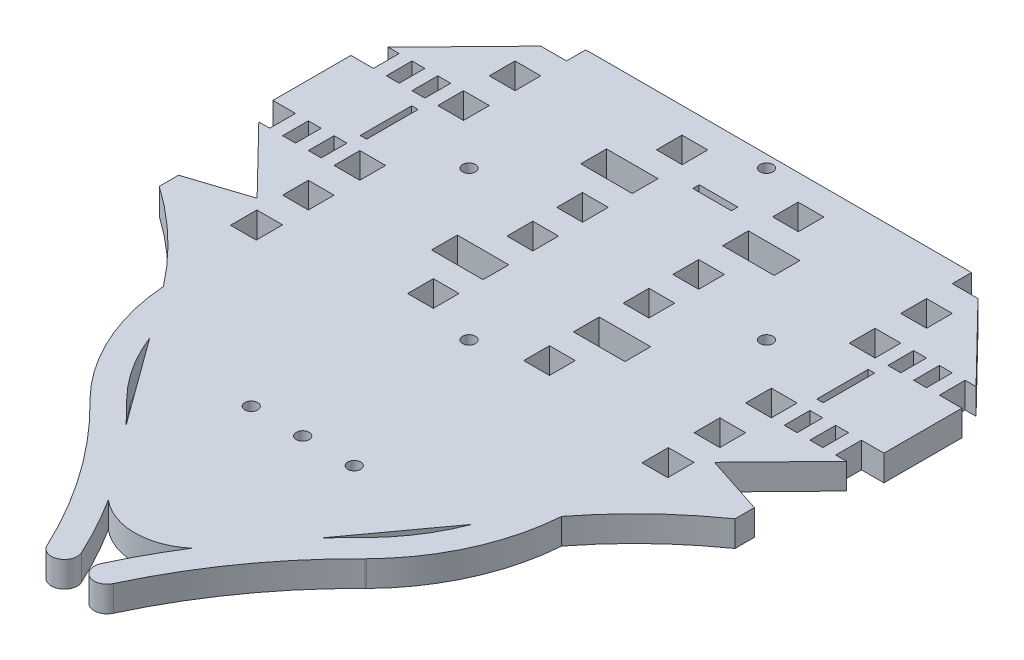
SolidWorks part; units mm, degrees
ref_plane "Front Plane" through (0, 0, 0) normal (0, 0, 1) x (1, 0, 0)
ref_plane "Top Plane" through (0, 0, 0) normal (0, 1, 0) x (1, 0, 0)
ref_plane "Right Plane" through (0, 0, 0) normal (1, 0, 0) x (0, 0, -1)
sketch "Sketch1" plane through (0, 0, 0) normal (0, 1, 0) x (1, 0, 0)
  line L0 (0, 0) -> (0, 190.5) construction
  line L1 (-75.3541, 160.3375) -> (-75.3541, 141.1116)
  line L2 (-11.1506, 184.15) -> (-11.1506, 177.85)
  line L3 (-17.5006, 184.15) -> (-11.1506, 184.15)
  line L4 (47.5742, 185.7375) -> (47.5742, 190.4453)
  line L5 (-53.9242, 160.3375) -> (-53.9242, 166.6875) construction
  line L6 (-31.7501, 150.7245) -> (31.7501, 150.7245) construction
  line L7 (47.5742, 173.0375) -> (47.5742, 179.3875)
  line L8 (-45.218, 190.5) -> (45.218, 190.5)
  line L9 (47.5742, 160.3375) -> (47.5742, 166.6875)
  line L10 (47.5742, 160.3375) -> (47.5742, 141.1116) construction
  line L11 (-39.7923, 75.1534) -> (-23.9247, 53.3989)
  line L12 (47.5742, 141.1116) -> (47.5742, 134.7616)
  line L13 (0, 92.6888) -> (-28.0924, 92.6888) construction
  line L14 (47.5742, 128.4116) -> (47.5742, 122.0616)
  line L15 (-28.0924, 105.9095) -> (-21.7424, 105.9095)
  line L16 (-21.7424, 105.9095) -> (-21.7424, 118.6095)
  line L17 (21.7424, 105.9095) -> (21.7424, 118.6095)
  line L18 (28.0924, 105.9095) -> (21.7424, 105.9095)
  line L19 (11.1506, 184.15) -> (11.1506, 177.85) construction
  line L20 (11.1506, 122.809) -> (11.1506, 116.459)
  line L21 (-17.5006, 184.15) -> (-17.5006, 177.85) construction
  line L22 (-17.5006, 177.85) -> (-11.1506, 177.85)
  line L23 (11.1506, 147.3454) -> (11.1506, 140.9954)
  line L24 (21.7424, 79.4681) -> (21.7424, 66.7681)
  line L25 (28.0924, 79.4681) -> (21.7424, 79.4681)
  line L26 (-21.7424, 79.4681) -> (-21.7424, 66.7681)
  line L27 (-28.0924, 79.4681) -> (-21.7424, 79.4681)
  line L28 (17.5006, 116.459) -> (11.1506, 116.459)
  line L29 (17.5006, 122.809) -> (17.5006, 116.459) construction
  line L30 (17.5006, 122.809) -> (11.1506, 122.809)
  line L31 (11.1506, 159.6136) -> (11.1506, 153.2636)
  line L32 (-17.5006, 159.6136) -> (-11.1506, 159.6136)
  line L33 (-17.5006, 159.6136) -> (-17.5006, 153.2636) construction
  line L34 (-28.0924, 105.9095) -> (-28.0924, 118.6095)
  line L35 (21.7424, 118.6095) -> (28.0924, 118.6095)
  line L36 (28.0924, 105.9095) -> (28.0924, 118.6095)
  line L37 (21.7424, 66.7681) -> (28.0924, 66.7681)
  line L38 (-103.4465, 150.7245) -> (-84.8791, 150.7245) construction
  line L39 (-103.3706, 147.4616) -> (-84.8791, 147.4616) construction
  line L40 (-103.3546, 153.9875) -> (-84.8791, 153.9875) construction
  line L41 (-103.4465, 153.9875) -> (-84.8791, 153.9875) construction
  line L42 (-103.4465, 147.4616) -> (-84.8791, 147.4616) construction
  line L43 (-71.0143, 118.2516) -> (-71.0143, 108.732)
  line L44 (-53.9242, 173.0375) -> (-53.9242, 179.3875)
  line L45 (-53.9242, 160.3375) -> (-53.9242, 166.6875)
  line L46 (-53.9242, 109.2092) -> (-53.9242, 115.7116)
  line L47 (-84.8791, 150.7245) -> (-31.7501, 150.7245) construction
  line L48 (-47.5742, 160.3375) -> (-47.5742, 141.1116) construction
  line L49 (-53.9242, 115.7116) -> (-47.5742, 115.7116)
  line L50 (-72.4971, 166.6875) -> (-53.9242, 185.7375)
  line L51 (-53.9242, 134.7616) -> (-53.9242, 141.1116)
  line L52 (-53.9242, 118.2516) -> (-47.5742, 118.2516) construction
  line L53 (-53.9242, 122.0616) -> (-53.9242, 128.4116)
  line L54 (-57.0992, 134.7616) -> (-57.0992, 141.1116)
  line L55 (47.5742, 115.7116) -> (47.5742, 109.2092)
  line L56 (-71.0143, 118.2516) -> (-56.4006, 118.2516)
  line L57 (-60.2742, 134.7616) -> (-60.2742, 141.1116)
  line L58 (-63.4492, 134.7616) -> (-63.4492, 141.1116)
  line L59 (84.8791, 150.7245) -> (31.7501, 150.7245) construction
  line L60 (-47.5742, 166.6875) -> (-53.9242, 166.6875)
  line L61 (-47.5742, 160.3375) -> (-47.5742, 166.6875)
  line L62 (-47.5742, 160.3375) -> (-53.9242, 160.3375)
  line L63 (-47.5742, 173.0375) -> (-53.9242, 173.0375)
  line L64 (-47.5742, 179.3875) -> (-53.9242, 179.3875)
  line L65 (-47.5742, 185.7375) -> (-53.9242, 185.7375)
  line L66 (-47.5742, 173.0375) -> (-47.5742, 179.3875)
  line L67 (103.3546, 153.9875) -> (84.8791, 153.9875) construction
  line L68 (-47.5742, 185.7375) -> (-47.5742, 190.4453)
  line L69 (-66.6242, 134.7616) -> (-66.6242, 141.1116)
  line L70 (-47.5742, 115.7116) -> (-47.5742, 109.2092)
  line L71 (-69.7992, 134.7616) -> (-69.7992, 141.1116)
  line L72 (-47.5742, 128.4116) -> (-47.5742, 122.0616)
  line L73 (-47.5742, 122.0616) -> (-53.9242, 122.0616)
  line L74 (-47.5742, 128.4116) -> (-53.9242, 128.4116)
  line L75 (-47.5742, 141.1116) -> (-53.9242, 141.1116)
  line L76 (-47.5742, 141.1116) -> (-47.5742, 134.7616)
  line L77 (-47.5742, 134.7616) -> (-53.9242, 134.7616)
  line L78 (-69.7992, 160.3375) -> (-75.3541, 160.3375)
  line L79 (-47.5742, 109.2092) -> (-53.9242, 109.2092)
  line L80 (-17.5006, 153.2636) -> (-11.1506, 153.2636)
  line L81 (-17.5006, 147.3454) -> (-11.1506, 147.3454)
  line L82 (-17.5006, 147.3454) -> (-17.5006, 140.9954) construction
  line L83 (-17.5006, 140.9954) -> (-11.1506, 140.9954)
  line L84 (-11.1506, 159.6136) -> (-11.1506, 153.2636)
  line L85 (-17.5006, 122.809) -> (-11.1506, 122.809)
  line L86 (-17.5006, 122.809) -> (-17.5006, 116.459) construction
  line L87 (-17.5006, 116.459) -> (-11.1506, 116.459)
  line L88 (-11.1506, 147.3454) -> (-11.1506, 140.9954)
  line L89 (-11.1506, 122.809) -> (-11.1506, 116.459)
  line L90 (-57.0992, 134.7616) -> (-60.2742, 134.7616)
  line L91 (-57.0992, 141.1116) -> (-60.2742, 141.1116)
  line L92 (-63.4492, 141.1116) -> (-66.6242, 141.1116)
  line L93 (23.8506, 165.5318) -> (11.1506, 165.5318)
  line L94 (-11.1506, 165.5318) -> (-11.1506, 171.8818)
  line L95 (-23.8506, 171.8818) -> (-11.1506, 171.8818) construction
  line L96 (23.8506, 165.5318) -> (23.8506, 171.8818)
  line L97 (23.8506, 171.8818) -> (11.1506, 171.8818) construction
  line L98 (-23.8506, 165.5318) -> (-23.8506, 171.8818)
  line L99 (11.1506, 165.5318) -> (11.1506, 171.8818)
  line L100 (-23.8506, 165.5318) -> (-11.1506, 165.5318)
  line L101 (-63.4492, 134.7616) -> (-66.6242, 134.7616)
  line L102 (-17.5006, 184.15) -> (-17.5006, 177.85)
  line L103 (-69.7992, 134.7616) -> (-72.4971, 134.7616)
  line L104 (-69.7992, 141.1116) -> (-75.3541, 141.1116)
  line L105 (-23.8506, 150.3045) -> (23.8506, 150.3045) construction
  line L106 (-23.8506, 135.0772) -> (-11.1506, 135.0772)
  line L107 (17.5006, 140.9954) -> (11.1506, 140.9954)
  line L108 (17.5006, 147.3454) -> (17.5006, 140.9954) construction
  line L109 (17.5006, 147.3454) -> (11.1506, 147.3454)
  line L110 (11.1506, 135.0772) -> (11.1506, 128.7272)
  line L111 (17.5006, 153.2636) -> (11.1506, 153.2636)
  line L112 (17.5006, 159.6136) -> (17.5006, 153.2636) construction
  line L113 (17.5006, 159.6136) -> (11.1506, 159.6136)
  line L114 (-23.8506, 135.0772) -> (-23.8506, 128.7272)
  line L115 (23.8506, 128.7272) -> (11.1506, 128.7272) construction
  line L116 (23.8506, 135.0772) -> (23.8506, 128.7272)
  line L117 (-23.8506, 128.7272) -> (-11.1506, 128.7272) construction
  line L118 (-11.1506, 135.0772) -> (-11.1506, 128.7272)
  line L119 (23.8506, 135.0772) -> (11.1506, 135.0772)
  line L120 (17.5006, 177.85) -> (11.1506, 177.85)
  line L121 (17.5006, 184.15) -> (17.5006, 177.85) construction
  line L122 (17.5006, 184.15) -> (11.1506, 184.15)
  line L123 (103.3706, 147.4616) -> (84.8791, 147.4616) construction
  line L124 (103.4465, 150.7245) -> (84.8791, 150.7245) construction
  line L125 (57.0992, 166.6875) -> (57.0992, 160.3375)
  line L126 (60.2742, 166.6875) -> (60.2742, 160.3375)
  line L127 (63.4492, 166.6875) -> (63.4492, 160.3375)
  line L128 (66.6242, 166.6875) -> (66.6242, 160.3375)
  line L129 (69.7992, 166.6875) -> (69.7992, 160.3375)
  line L130 (57.0992, 166.6875) -> (60.2742, 166.6875)
  line L131 (57.0992, 160.3375) -> (60.2742, 160.3375)
  line L132 (63.4492, 160.3375) -> (66.6242, 160.3375)
  line L133 (11.1506, 184.15) -> (11.1506, 177.85)
  line L134 (63.4492, 166.6875) -> (66.6242, 166.6875)
  line L135 (-72.4971, 134.7616) -> (-56.4006, 118.2516)
  line L136 (69.7992, 166.6875) -> (72.4971, 166.6875)
  line L137 (72.4971, 134.7616) -> (56.4006, 118.2516)
  line L138 (69.7992, 141.1116) -> (75.3541, 141.1116)
  line L139 (69.7992, 134.7616) -> (72.4971, 134.7616)
  line L140 (63.4492, 134.7616) -> (66.6242, 134.7616)
  line L141 (63.4492, 141.1116) -> (66.6242, 141.1116)
  line L142 (57.0992, 141.1116) -> (60.2742, 141.1116)
  line L143 (57.0992, 134.7616) -> (60.2742, 134.7616)
  line L144 (47.5742, 109.2092) -> (53.9242, 109.2092)
  line L145 (69.7992, 160.3375) -> (75.3541, 160.3375)
  line L146 (47.5742, 134.7616) -> (53.9242, 134.7616)
  line L147 (-69.7992, 166.6875) -> (-72.4971, 166.6875)
  line L148 (47.5742, 141.1116) -> (53.9242, 141.1116)
  line L149 (47.5742, 128.4116) -> (53.9242, 128.4116)
  line L150 (47.5742, 122.0616) -> (53.9242, 122.0616)
  line L151 (-63.4492, 166.6875) -> (-66.6242, 166.6875)
  line L152 (69.7992, 134.7616) -> (69.7992, 141.1116)
  line L153 (66.6242, 134.7616) -> (66.6242, 141.1116)
  line L154 (47.5742, 185.7375) -> (53.9242, 185.7375)
  line L155 (-63.4492, 160.3375) -> (-66.6242, 160.3375)
  line L156 (47.5742, 179.3875) -> (53.9242, 179.3875)
  line L157 (-57.0992, 160.3375) -> (-60.2742, 160.3375)
  line L158 (-57.0992, 166.6875) -> (-60.2742, 166.6875)
  line L159 (47.5742, 173.0375) -> (53.9242, 173.0375)
  line L160 (-23.8506, 171.8818) -> (-11.1506, 171.8818)
  line L161 (-69.7992, 166.6875) -> (-69.7992, 160.3375)
  line L162 (-66.6242, 166.6875) -> (-66.6242, 160.3375)
  line L163 (-63.4492, 166.6875) -> (-63.4492, 160.3375)
  line L164 (-60.2742, 166.6875) -> (-60.2742, 160.3375)
  line L165 (-57.0992, 166.6875) -> (-57.0992, 160.3375)
  line L166 (-17.5006, 159.6136) -> (-17.5006, 153.2636)
  line L167 (39.7923, 75.1534) -> (23.9247, 53.3989)
  line L168 (47.5742, 160.3375) -> (53.9242, 160.3375)
  line L169 (47.5742, 166.6875) -> (53.9242, 166.6875)
  line L170 (-28.0924, 66.7681) -> (-21.7424, 66.7681)
  line L171 (-28.0924, 66.7681) -> (-28.0924, 79.4681)
  line L172 (63.4492, 134.7616) -> (63.4492, 141.1116)
  line L173 (-28.0924, 118.6095) -> (-21.7424, 118.6095)
  line L174 (28.0924, 66.7681) -> (28.0924, 79.4681)
  line L175 (-28.0924, 66.7681) -> (28.0924, 118.6095) construction
  line L176 (-28.0924, 118.6095) -> (28.0924, 66.7681) construction
  line L177 (-17.5006, 147.3454) -> (-17.5006, 140.9954)
  line L178 (60.2742, 134.7616) -> (60.2742, 141.1116)
  line L179 (71.0143, 118.2516) -> (56.4006, 118.2516)
  line L180 (57.0992, 134.7616) -> (57.0992, 141.1116)
  line L181 (53.9242, 122.0616) -> (53.9242, 128.4116)
  line L182 (53.9242, 134.7616) -> (53.9242, 141.1116)
  line L183 (72.4971, 166.6875) -> (53.9242, 185.7375)
  line L184 (-23.8506, 128.7272) -> (-11.1506, 128.7272)
  line L185 (53.9242, 115.7116) -> (47.5742, 115.7116)
  line L186 (53.9242, 109.2092) -> (53.9242, 115.7116)
  line L187 (-17.5006, 122.809) -> (-17.5006, 116.459)
  line L188 (53.9242, 160.3375) -> (53.9242, 166.6875)
  line L189 (53.9242, 173.0375) -> (53.9242, 179.3875)
  line L190 (71.0143, 118.2516) -> (71.0143, 108.732)
  line L191 (17.5006, 116.459) -> (17.5006, 122.809)
  line L192 (75.3541, 160.3375) -> (75.3541, 141.1116)
  line L193 (57.0992, 157.0745) -> (55.5117, 157.0745)
  line L194 (11.1506, 128.7272) -> (23.8506, 128.7272)
  line L195 (-14.3256, 184.15) -> (-14.3256, 190.5) construction
  line L196 (-14.3256, 187.325) -> (14.3256, 187.325) construction
  line L197 (57.0992, 144.3745) -> (57.0992, 157.0745)
  line L198 (55.5117, 144.3745) -> (55.5117, 157.0745)
  line L199 (17.5006, 140.9954) -> (17.5006, 147.3454)
  line L200 (-55.5117, 144.3745) -> (-57.0992, 144.3745)
  line L201 (-55.5117, 144.3745) -> (-55.5117, 157.0745)
  line L202 (-57.0992, 157.0745) -> (-55.5117, 157.0745)
  line L203 (17.5006, 153.2636) -> (17.5006, 159.6136)
  line L204 (55.5117, 144.3745) -> (57.0992, 144.3745)
  line L205 (-11.1506, 177.85) -> (-11.1506, 171.8818) construction
  line L206 (11.1506, 171.8818) -> (23.8506, 171.8818)
  line L207 (-11.1506, 174.8659) -> (0, 174.8659) construction
  line L208 (-57.0992, 144.3745) -> (-57.0992, 157.0745)
  line L210 (-4.7625, 174.0722) -> (4.7625, 174.0722)
  line L211 (17.5006, 177.85) -> (17.5006, 184.15)
  line L212 (-4.7625, 174.0722) -> (-4.7625, 175.6597)
  line L213 (-4.7625, 175.6597) -> (4.7625, 175.6597)
  line L214 (4.7625, 174.0722) -> (4.7625, 175.6597)
  line L215 (-72.9742, 135.2509) -> (-72.9742, 141.1116) [skipped]
  line L216 (-21.7424, 73.1181) -> (21.7424, 73.1181) construction
  line L217 (-4.7625, 174.0722) -> (4.7625, 175.6597) construction
  line L218 (-4.7625, 175.6597) -> (4.7625, 174.0722) construction
  arc A0 (-98.3796, 168.1096) -> (-103.3546, 153.9875) centre (-71.7653, 150.7966) ccw construction
  arc A1 (-10.307, 35.463) -> (10.307, 35.463) centre (0, 47.625) ccw
  arc A2 (-103.3706, 147.4616) -> (-78.8191, 113.9815) centre (-63.8175, 150.7245) ccw construction
  arc A3 (-70.6509, 186.2152) -> (-98.3796, 168.1096) centre (-67.31, 150.8125) ccw construction
  arc A4 (-71.0143, 108.732) -> (-49.1129, 87.8559) centre (-129.382, 25.5708) cw
  arc A5 (47.5742, 190.4453) -> (45.218, 190.5) centre (45.218, 139.7) ccw
  arc A6 (66.2518, 115.2682) -> (31.7501, 150.7245) centre (67.31, 150.8125) cw construction
  arc A7 (-67.31, 186.3725) -> (-31.7501, 150.7245) centre (-67.31, 150.8125) cw construction
  arc A8 (-66.2518, 115.2682) -> (-31.7501, 150.7245) centre (-67.31, 150.8125) ccw construction
  arc A9 (67.31, 186.3725) -> (31.7501, 150.7245) centre (67.31, 150.8125) ccw construction
  arc A10 (70.6509, 186.2152) -> (98.3796, 168.1096) centre (67.31, 150.8125) cw construction
  arc A11 (103.3706, 147.4616) -> (78.8191, 113.9815) centre (63.8175, 150.7245) cw construction
  arc A12 (98.3796, 168.1096) -> (103.3546, 153.9875) centre (71.7653, 150.7966) cw construction
  arc A13 (71.0143, 108.732) -> (49.1129, 87.8559) centre (129.382, 25.5708) ccw
  arc A14 (23.9247, 53.3989) -> (29.4574, 59.1474) centre (120.746, -34.2501) cw
  arc A15 (34.0855, 54.7275) -> (33.9333, 54.5681) centre (31.6954, 56.8578) cw
  arc A16 (39.7923, 75.1534) -> (29.5378, 59.2233) centre (-3.4651, 91.7334) cw
  arc A17 (-47.5742, 190.4453) -> (-45.218, 190.5) centre (-45.218, 139.7) cw
  arc A18 (-2.3792, 20.9404) -> (-10.307, 35.463) centre (-120.746, -34.2501) ccw
  arc A19 (-8.1827, 18.2344) -> (-33.9333, 54.5681) centre (-120.746, -34.2501) ccw
  arc A20 (-8.1827, 18.2344) -> (-2.3792, 20.9404) centre (-5.2809, 19.5874) ccw
  arc A21 (-29.4574, 59.1474) -> (-29.5378, 59.2233) centre (-31.6954, 56.8578) ccw
  circle A22 centre (0, 150.7245) radius 36.6005 construction
  arc A23 (-49.1129, 87.8559) -> (-34.0855, 54.7275) centre (3.4651, 91.7334) ccw
  arc A24 (-39.7923, 75.1534) -> (-29.5378, 59.2233) centre (3.4651, 91.7334) ccw
  arc A25 (-34.0855, 54.7275) -> (-33.9333, 54.5681) centre (-31.6954, 56.8578) ccw
  arc A26 (-23.9247, 53.3989) -> (-29.4574, 59.1474) centre (-120.746, -34.2501) ccw
  arc A27 (49.1129, 87.8559) -> (34.0855, 54.7275) centre (-3.4651, 91.7334) cw
  circle A28 centre (0, 114.1241) radius 1.5875
  arc A29 (29.4574, 59.1474) -> (29.5378, 59.2233) centre (31.6954, 56.8578) cw
  circle A30 centre (-36.6884, 150.8125) radius 1.5875
  arc A31 (8.1827, 18.2344) -> (2.3792, 20.9404) centre (5.2809, 19.5874) cw
  arc A32 (8.1827, 18.2344) -> (33.9333, 54.5681) centre (120.746, -34.2501) cw
  arc A33 (2.3792, 20.9404) -> (10.307, 35.463) centre (120.746, -34.2501) cw
  circle A34 centre (0, 73.1031) radius 1.5875
  circle A35 centre (12.7, 73.1031) radius 1.5875
  circle A36 centre (0, 187.5009) radius 1.5875
  circle A37 centre (36.6884, 150.8125) radius 1.5875
  circle A38 centre (-12.7, 73.1031) radius 1.5875
  point P28 (-51.906, 190.5)
  point P30 (-67.31, 186.3725)
  point P32 (0, 150.8125)
  point P50 (-16.804, 39.5041)
  point P55 (-40.3772, 68.7904)
  point P67 (0, 75.2413)
  point P69 (0, 150.7245)
  point P96 (0, 92.6888)
  point P151 (0, 168.7068)
  point P154 (-14.3256, 168.7068)
  point P156 (-23.8506, 168.7068)
  point P177 (14.3256, 168.7068)
  point P180 (-23.8506, 150.3045)
  point P183 (-14.3256, 131.9022)
  point P211 (-53.9242, 150.7245)
  point P233 (14.3256, 131.9022)
  point P235 (0, 131.9022)
  point P256 (40.3772, 68.7904)
  point P257 (16.804, 39.5041)
  point P258 (53.9242, 150.7245)
  point P269 (-55.5117, 150.7245)
  point P271 (0, 178.6438)
  point P285 (0, 150.8125)
  point P289 (0, 180.975)
  dimension "D4" = 6.35
  dimension "D5" = 51.8414
  dimension "D6" = 56.1848
  dimension "D7" = 79.375
  dimension "D8" = 71.12
  dimension "D9" = 12.7
  dimension "D11" = 2.54
  dimension "D12" = 6
  dimension "D13" = 9.525
  dimension "D14" = 3.175
  dimension "D17" = 1.5875
  dimension "D3" = 4
  dimension "D10" = 3.175
  dimension "D16" = 18.5674
  dimension "D19" = 6.35
  dimension "D23" = 2
  dimension "D18" = 6.35
  dimension "D20" = 6.35
  dimension "D15" = 1.5875
  dimension "D21" = 12.7
  dimension "D22" = 2
  dimension "D24" = 2
extrude "Boss-Extrude1" add sketch "Sketch1" along normal blind 6.35
sketch "Sketch2" plane through (0, 6.35, 0) normal (0, 1, 0) x (1, 0, 0)
  line L0 (-56.4006, 118.2516) -> (-71.0143, 118.2516)
  line L1 (-71.0143, 118.2516) -> (-71.0143, 113.4918)
  line L2 (-71.0143, 118.2516) -> (-71.0143, 108.732) construction
  line L3 (-71.0143, 113.4918) -> (-56.4006, 118.2516)
  line L4 (0, 189.0884) -> (0, 90.2888) construction
  line L5 (71.0143, 113.4918) -> (56.4006, 118.2516)
  line L6 (71.0143, 118.2516) -> (71.0143, 113.4918)
  line L7 (56.4006, 118.2516) -> (71.0143, 118.2516)
  circle A0 centre (0, 187.5009) radius 1.5875 construction
extrude "Cut-Extrude1" cut sketch "Sketch2" against normal through all
sketch "Sketch3" plane through (0, 6.35, 0) normal (0, 1, 0) x (1, 0, 0)
  line L0 (-21.7424, 118.6095) -> (-28.0924, 118.6095) construction
  line L1 (-28.0924, 118.6095) -> (-28.0924, 105.9095) construction
  line L2 (-28.0924, 105.9095) -> (-21.7424, 105.9095) construction
  line L3 (-21.7424, 105.9095) -> (-21.7424, 118.6095) construction
  line L4 (21.7424, 118.6095) -> (21.7424, 105.9095) construction
  line L5 (28.0924, 118.6095) -> (21.7424, 118.6095) construction
  line L6 (28.0924, 105.9095) -> (28.0924, 118.6095) construction
  line L7 (21.7424, 105.9095) -> (28.0924, 105.9095) construction
  line L8 (28.0924, 79.4681) -> (21.7424, 79.4681) construction
  line L9 (21.7424, 79.4681) -> (21.7424, 66.7681) construction
  line L10 (28.0924, 66.7681) -> (28.0924, 79.4681) construction
  line L11 (21.7424, 66.7681) -> (28.0924, 66.7681) construction
  line L12 (-28.0924, 66.7681) -> (-21.7424, 66.7681) construction
  line L13 (-28.0924, 79.4681) -> (-28.0924, 66.7681) construction
  line L14 (-21.7424, 79.4681) -> (-28.0924, 79.4681) construction
  line L15 (-21.7424, 66.7681) -> (-21.7424, 79.4681) construction
  line L16 (-21.7424, 118.6095) -> (-28.0924, 118.6095)
  line L17 (-28.0924, 118.6095) -> (-28.0924, 105.9095)
  line L18 (-28.0924, 105.9095) -> (-21.7424, 105.9095)
  line L19 (-21.7424, 105.9095) -> (-21.7424, 118.6095)
  line L20 (21.7424, 118.6095) -> (21.7424, 105.9095)
  line L21 (28.0924, 118.6095) -> (21.7424, 118.6095)
  line L22 (28.0924, 105.9095) -> (28.0924, 118.6095)
  line L23 (21.7424, 105.9095) -> (28.0924, 105.9095)
  line L24 (28.0924, 79.4681) -> (21.7424, 79.4681)
  line L25 (21.7424, 79.4681) -> (21.7424, 66.7681)
  line L26 (28.0924, 66.7681) -> (28.0924, 79.4681)
  line L27 (21.7424, 66.7681) -> (28.0924, 66.7681)
  line L28 (-28.0924, 66.7681) -> (-21.7424, 66.7681)
  line L29 (-28.0924, 79.4681) -> (-28.0924, 66.7681)
  line L30 (-21.7424, 79.4681) -> (-28.0924, 79.4681)
  line L31 (-21.7424, 66.7681) -> (-21.7424, 79.4681)
extrude "Boss-Extrude2" add sketch "Sketch3" against normal blind 2.54
